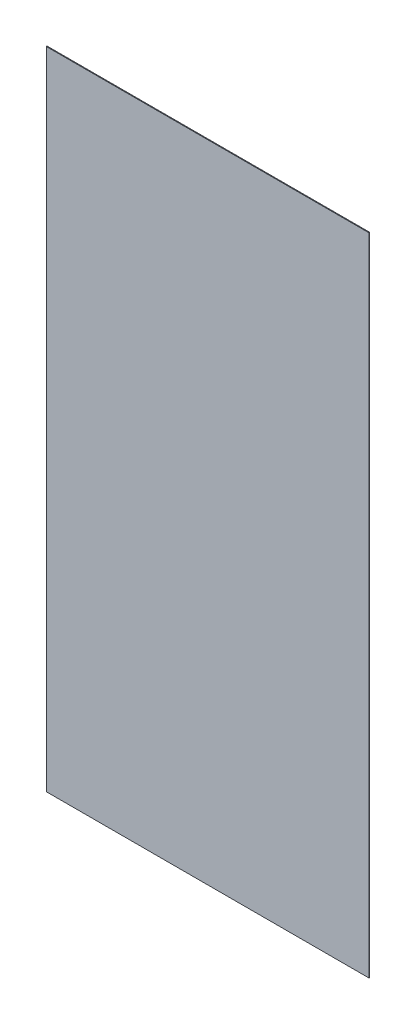
SolidWorks part; units mm, degrees
ref_plane "Front Plane" through (0, 0, 0) normal (0, 0, 1) x (1, 0, 0)
ref_plane "Top Plane" through (0, 0, 0) normal (0, 1, 0) x (1, 0, 0)
ref_plane "Right Plane" through (0, 0, 0) normal (1, 0, 0) x (0, 0, -1)
sketch "Sketch1" plane through (0, 0, 0) normal (0, 0, 1) x (1, 0, 0)
  line L0 (0, 1219.2) -> (609.6, 1219.2) construction
  line L1 (-609.6, 1219.2) -> (609.6, 1219.2)
  line L2 (-609.6, 1219.2) -> (-609.6, -1219.2)
  line L3 (-609.6, -1219.2) -> (609.6, -1219.2)
  line L4 (609.6, 1219.2) -> (609.6, -1219.2)
  line L5 (-609.6, 1219.2) -> (609.6, -1219.2) construction
  line L6 (-609.6, -1219.2) -> (609.6, 1219.2) construction
  line L7 (-609.6, 1219.2) -> (0, 1219.2) construction
  line L8 (-609.6, 1219.2) -> (-609.6, 0) construction
  line L9 (-609.6, 0) -> (0, 0) construction
  line L10 (0, 1219.2) -> (0, 0) construction
  line L11 (0, 1219.2) -> (0, 0) construction
  line L12 (0, 0) -> (609.6, 0) construction
  line L13 (609.6, 1219.2) -> (609.6, 0) construction
  line L14 (-609.6, 0) -> (0, 0) construction
  line L15 (-609.6, 0) -> (-609.6, -1219.2) construction
  line L16 (-609.6, -1219.2) -> (0, -1219.2) construction
  line L17 (0, 0) -> (0, -1219.2) construction
  line L18 (0, 0) -> (609.6, 0) construction
  line L19 (0, 0) -> (0, -1219.2) construction
  line L20 (0, -1219.2) -> (609.6, -1219.2) construction
  line L21 (609.6, 0) -> (609.6, -1219.2) construction
  point P0 (0, 0)
  point P6 (0, 1196.7915)
  point P10 (0, 0)
  point P11 (-1910.3526, 1106.8803)
  point P16 (-631.6148, 1219.2)
  point P20 (-588.3242, 0)
  point P22 (-1657.2691, 34.6054)
  point P25 (7.6889, -15.3778)
  dimension "D1" = 1219.2
  dimension "D2" = 2438.4
  dimension "D3" = 609.6
  dimension "D4" = 1219.2
  dimension "D5" = 609.6
  dimension "D6" = 1219.2
  dimension "D7" = 609.6
  dimension "D8" = 1219.2
  dimension "D9" = 609.6
  dimension "D10" = 1219.2
extrude "Boss-Extrude1" add sketch "Sketch1" along normal blind 2.9972
